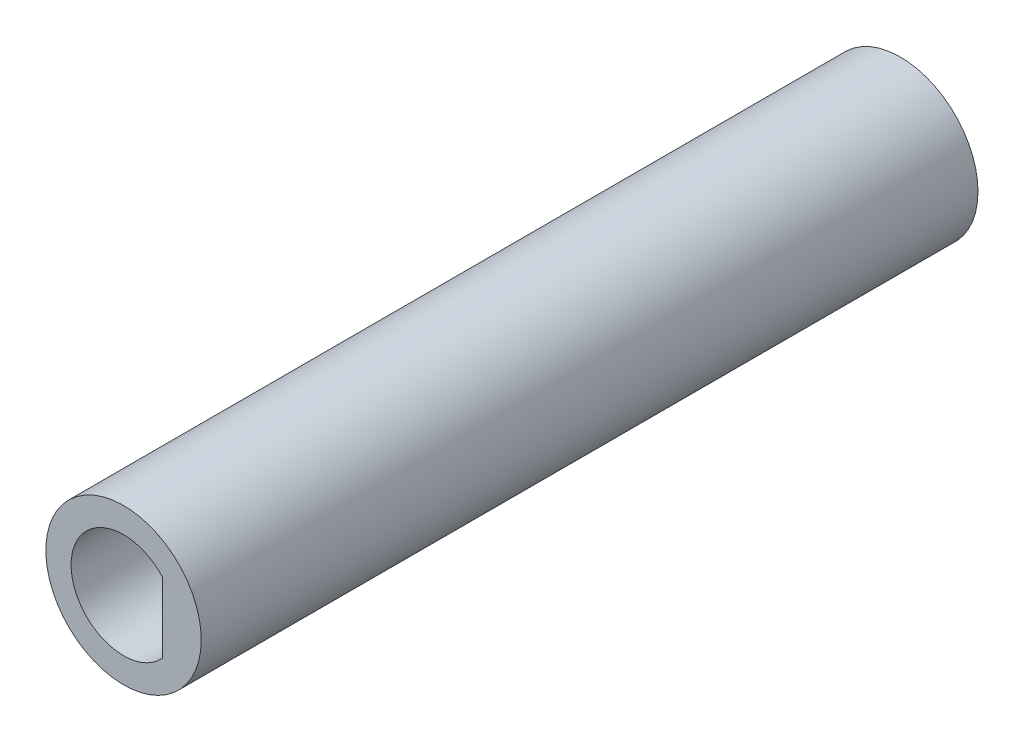
SolidWorks part; units mm, degrees
ref_plane "Front Plane" through (0, 0, 0) normal (0, 0, 1) x (1, 0, 0)
ref_plane "Top Plane" through (0, 0, 0) normal (0, 1, 0) x (1, 0, 0)
ref_plane "Right Plane" through (0, 0, 0) normal (1, 0, 0) x (0, 0, -1)
sketch "Sketch1" plane through (0, 0, 0) normal (0, 0, 1) x (1, 0, 0)
  line L0 (3, 2.7208) -> (3, -2.7208)
  circle A1 centre (0, 0) radius 6
  arc A2 (3, 2.7208) -> (3, -2.7208) centre (0, 0) ccw
  dimension "D1" = 12
  dimension "D2" = 4.05
  dimension "D3" = 3
extrude "Boss-Extrude1" add sketch "Sketch1" along normal blind 15
sketch "Sketch2" plane through (0, 0, 0) normal (0, 0, 1) x (1, 0, 0)
  circle A0 centre (0, 0) radius 6
  circle A1 centre (0, 0) radius 6 construction
extrude "Boss-Extrude2" add sketch "Sketch2" against normal blind 45
ref_plane "Plane5" through (0, 0, -45) normal (0, 0, -1) x (-1, 0, 0)
sketch "Sketch38" plane through (0, 0, -45) normal (0, 0, -1) x (-1, 0, 0)
  line L0 (-6, 0) -> (6, 0) construction
  line L1 (0, 6) -> (0, -6) construction
  circle A0 centre (0, 0) radius 6 construction
